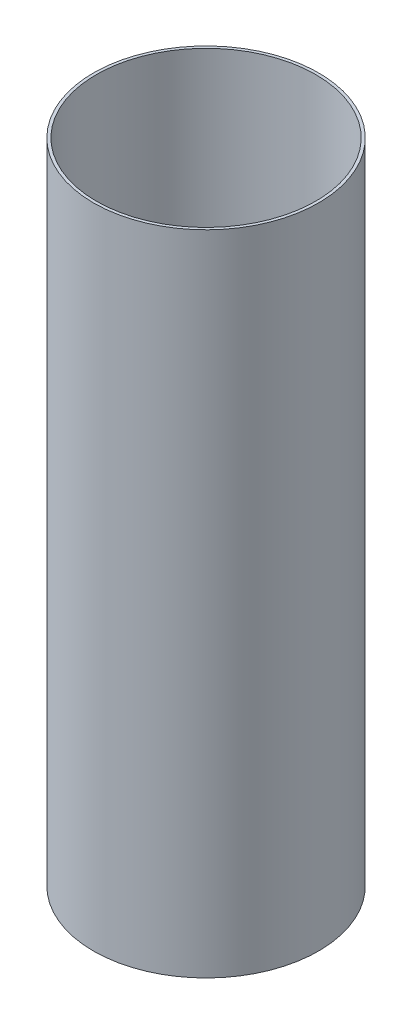
SolidWorks part; units mm, degrees
material "Thornel Mat VMA"
ref_plane "Front Plane" through (0, 0, 0) normal (0, 0, 1) x (1, 0, 0)
ref_plane "Top Plane" through (0, 0, 0) normal (0, 1, 0) x (1, 0, 0)
ref_plane "Right Plane" through (0, 0, 0) normal (1, 0, 0) x (0, 0, -1)
sketch "Sketch1" plane through (0, 0, 0) normal (0, 1, 0) x (1, 0, 0)
  circle A0 centre (0, 0) radius 76.2
  circle A1 centre (0, 0) radius 78.2
  dimension "D1" = 2
  dimension "D2" = 152.4
extrude "Boss-Extrude1" add sketch "Sketch1" along normal blind 450
